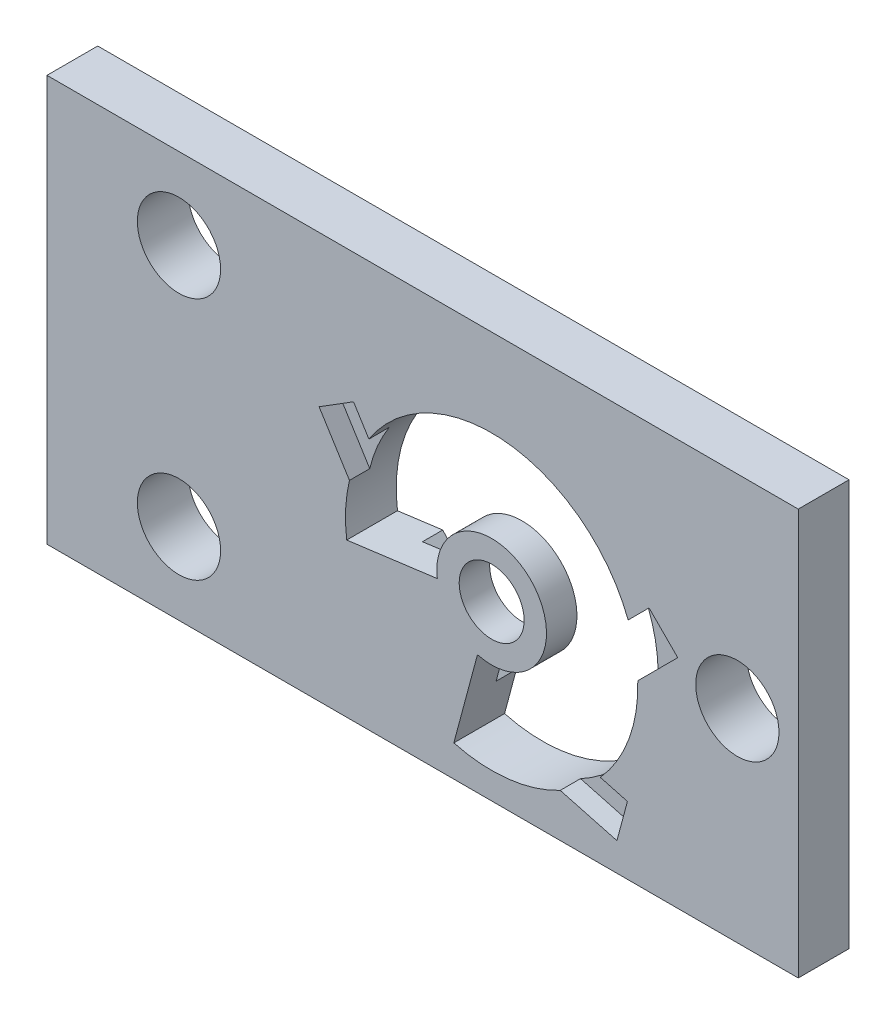
SolidWorks part; units mm, degrees
ref_plane "Plan de face" through (0, 0, 0) normal (0, 0, 1) x (1, 0, 0)
ref_plane "Plan de dessus" through (0, 0, 0) normal (0, 1, 0) x (1, 0, 0)
ref_plane "Plan de droite" through (0, 0, 0) normal (1, 0, 0) x (0, 0, -1)
sketch "Esquisse1" plane through (0, 0, 0) normal (0, 0, 1) x (1, 0, 0)
  line L0 (-12, 6) -> (-12, -6) construction
  line L1 (18.5, -10) -> (-18.5, -10)
  line L2 (18.5, -10) -> (18.5, 10)
  line L3 (18.5, 10) -> (-18.5, 10)
  line L4 (-18.5, -10) -> (-18.5, 10)
  line L5 (18.5, -10) -> (-18.5, 10) construction
  line L6 (18.5, 10) -> (-18.5, -10) construction
  line L7 (-3.7384, -2.44) -> (0.7231, -1.8525)
  line L8 (2.7012, -4.108) -> (1.5365, -8.4547)
  line L9 (3.4, -1.5) -> (3.4, -14.822) construction
  circle A0 centre (-12, 6) radius 2.05
  circle A1 centre (-12, -6) radius 2.05
  circle A2 centre (15.5, 0) radius 2.05
  circle A3 centre (3.4, -1.5) radius 8 construction
  arc A4 (1.5365, -8.4547) -> (-3.7384, -2.44) centre (3.4, -1.5) ccw construction
  arc A5 (2.7012, -4.108) -> (0.7231, -1.8525) centre (3.4, -1.5) ccw
  arc A6 (-3.7384, -2.44) -> (1.5365, -8.4547) centre (3.4, -1.5) cw
  circle A7 centre (3.4, -1.5) radius 1.6
  point P0 (0, 0)
  point P13 (-12, 0)
  point P23 (0, 0)
  point P24 (6.0405, -8.5106)
  dimension "D3" = 4.1
  dimension "D8" = 16
  dimension "D9" = 11.5
  dimension "D10" = 15.1
  dimension "D12" = 0.8
  dimension "D14" = 3.2
  dimension "D1" = 37
  dimension "D2" = 20
  dimension "D4" = 12
  dimension "D5" = 27.5
  dimension "D6" = 4
  dimension "D7" = 6.5
  dimension "D13" = 3
  dimension "D15" = 15
  dimension "D11" = 4.5
extrude "Boss.-Extru.1" add sketch "Esquisse1" along normal blind 2.5 contours L4 L1 L2 L3 A2 A1 A0 L7 A6 L8 A5
sketch "Esquisse3" plane through (0, 0, 0) normal (0, 0, -1) x (-1, 0, 0)
  line L0 (3.7384, -2.44) -> (-0.7231, -1.8525) construction
  line L1 (-2.7012, -4.108) -> (-1.5365, -8.4547) construction
  line L2 (3.7384, -2.44) -> (1.5076, -2.1463)
  line L3 (-2.1188, -6.2813) -> (-1.5365, -8.4547)
  line L4 (18.5, -10) -> (18.5, 10)
  line L5 (18.5, 10) -> (-18.5, 10)
  line L6 (-18.5, 10) -> (-18.5, -10)
  line L7 (-18.5, -10) -> (18.5, -10)
  line L8 (18.5, -10) -> (18.5, 10)
  line L9 (18.5, 10) -> (-18.5, 10)
  line L10 (-18.5, 10) -> (-18.5, -10)
  line L11 (-18.5, -10) -> (18.5, -10)
  line L12 (-2.1188, -6.2813) -> (1.5076, -2.1463)
  arc A2 (3.7384, -2.44) -> (-1.5365, -8.4547) centre (-3.4, -1.5) ccw construction
  arc A3 (3.7384, -2.44) -> (-1.5365, -8.4547) centre (-3.4, -1.5) ccw
  point P7 (-0.7333, -6.3254)
  dimension "D1" = 0
extrude "Enlèv. mat.-Extru.1" cut sketch "Esquisse3" against normal blind 1
sketch "Esquisse4" plane through (0, 0, 2.5) normal (0, 0, 1) x (1, 0, 0)
  line L0 (-5.0985, 2.5651) -> (-3.4024, 3.625)
  line L1 (-5.0985, 2.5651) -> (-2.9788, -0.8271)
  line L2 (-3.4024, 3.625) -> (-1.2827, 0.2328)
  line L3 (-2.9788, -0.8271) -> (-1.2827, 0.2328)
  line L4 (-3.4024, 3.625) -> (-2.9788, -0.8271) construction
  line L5 (0, 0.4891) -> (0, 15.2798) construction
  line L6 (-3.7384, -2.44) -> (0.7231, -1.8525) construction
  line L7 (11.1515, 2.1099) -> (12.5658, 0.6957)
  line L8 (11.1515, 2.1099) -> (8.3231, -0.7185)
  line L9 (12.5658, 0.6957) -> (9.7373, -2.1327)
  line L10 (8.3231, -0.7185) -> (9.7373, -2.1327)
  line L11 (11.1515, 2.1099) -> (9.7373, -2.1327) construction
  line L12 (10.0868, -6.6753) -> (9.5692, -8.6071)
  line L13 (10.0868, -6.6753) -> (6.2231, -5.64)
  line L14 (9.5692, -8.6071) -> (5.7055, -7.5719)
  line L15 (6.2231, -5.64) -> (5.7055, -7.5719)
  line L16 (10.0868, -6.6753) -> (5.7055, -7.5719) construction
  arc A0 (1.5365, -8.4547) -> (-3.7384, -2.44) centre (3.4, -1.5) ccw construction
  point P0 (-3.1906, 1.3989)
  point P9 (10.4444, -0.0114)
  point P12 (9.7279, -2.0889)
  point P13 (7.8961, -7.1236)
  point P24 (6.6616, -5.6833)
  dimension "D1" = 4
  dimension "D2" = 2
  dimension "D3" = 32
  dimension "D4" = 1.5
  dimension "D5" = 2
  dimension "D6" = 4
  dimension "D7" = 45
  dimension "D8" = 7.6
  dimension "D9" = 2
  dimension "D10" = 4
  dimension "D11" = 105
  dimension "D12" = 5.5
extrude "Enlèv. mat.-Extru.2" cut sketch "Esquisse4" against normal blind 1
ref_plane "Plan1" through (18.5, 0, 0) normal (1, 0, 0) x (0, 0, -1)
